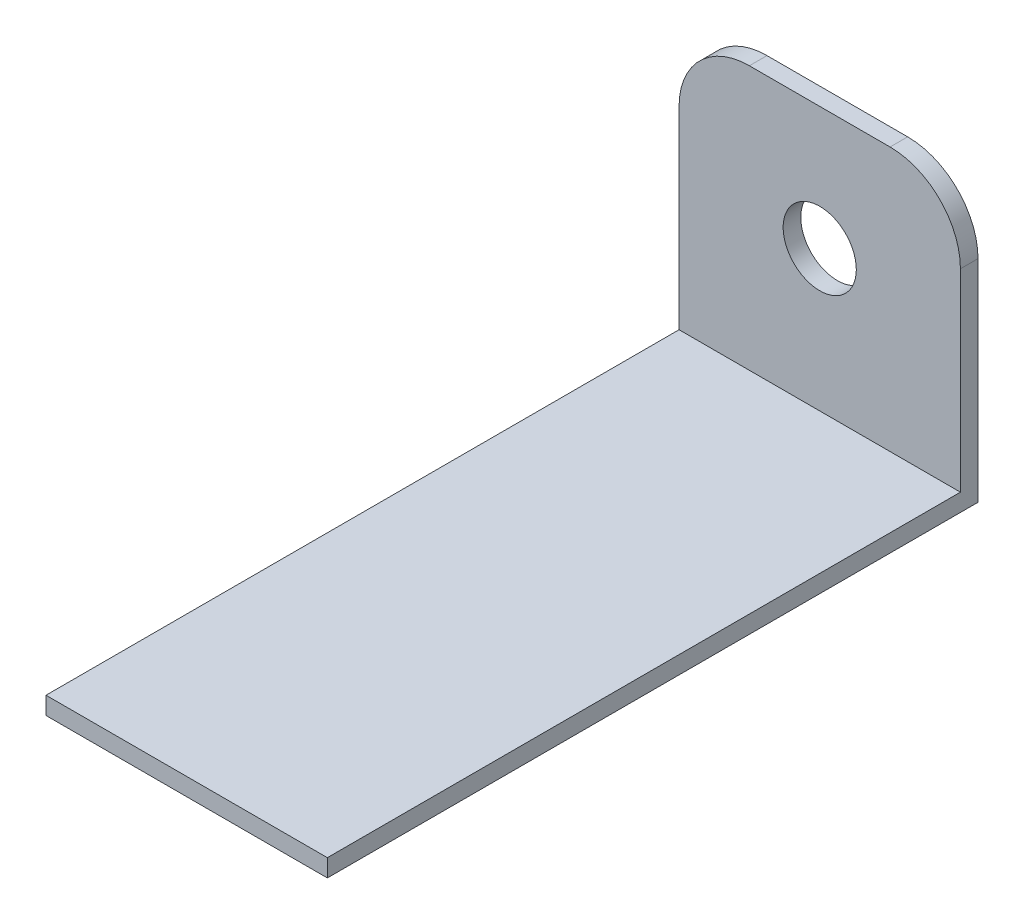
SolidWorks part; units mm, degrees
material "AISI 4130 Steel, annealed at 865C"
ref_plane "Front Plane" through (0, 0, 0) normal (0, 0, 1) x (1, 0, 0)
ref_plane "Top Plane" through (0, 0, 0) normal (0, 1, 0) x (1, 0, 0)
ref_plane "Right Plane" through (0, 0, 0) normal (1, 0, 0) x (0, 0, -1)
sketch "Sketch1" plane through (0, 0, 0) normal (0, 1, 0) x (1, 0, 0)
  line L1 (0, 0) -> (25.4, 0)
  line L2 (0, 0) -> (0, 57.15)
  line L3 (0, 57.15) -> (25.4, 57.15)
  line L4 (25.4, 0) -> (25.4, 57.15)
  line L5 (0, 0) -> (25.4, 57.15) construction
  line L6 (0, 57.15) -> (25.4, 0) construction
  point P4 (12.7, 28.575)
  dimension "D1" = 25.4
  dimension "D2" = 57.15
extrude "Boss-Extrude1" add sketch "Sketch1" along normal blind 1.5875
sketch "Sketch2" plane through (0, 0, -57.15) normal (0, 0, -1) x (-1, 0, 0)
  line L1 (-25.4, 0) -> (0, 0)
  line L2 (-25.4, 0) -> (-25.4, 25.4)
  line L3 (-25.4, 25.4) -> (0, 25.4)
  line L4 (0, 0) -> (0, 25.4)
  line L5 (-25.4, 0) -> (0, 25.4) construction
  line L6 (-25.4, 25.4) -> (0, 0) construction
  point P4 (-12.7, 12.7)
  dimension "D1" = 25.4
extrude "Boss-Extrude2" add sketch "Sketch2" along normal blind 1.5875
sketch "Sketch3" plane through (0, 0, -57.15) normal (0, 0, 1) x (1, 0, 0)
  line L0 (12.7, 1.5875) -> (12.7, 14.2875) construction
  line L1 (0, 25.4) -> (25.4, 25.4) construction
  line L2 (0, 25.4) -> (0, 1.5875) construction
  line L3 (0, 1.5875) -> (25.4, 1.5875) construction
  line L4 (25.4, 25.4) -> (25.4, 1.5875) construction
  line L5 (0, 25.4) -> (25.4, 1.5875) construction
  line L6 (0, 1.5875) -> (25.4, 25.4) construction
  circle A1 centre (12.7, 14.2875) radius 3.302
  dimension "D1" = 6.604
  dimension "D2" = 12.7
extrude "Cut-Extrude1" cut sketch "Sketch3" against normal through all
fillet "Fillet1" radius 6.35 2 edges at (25.4, 25.4, -57.9438) (0, 25.4, -57.9438)
